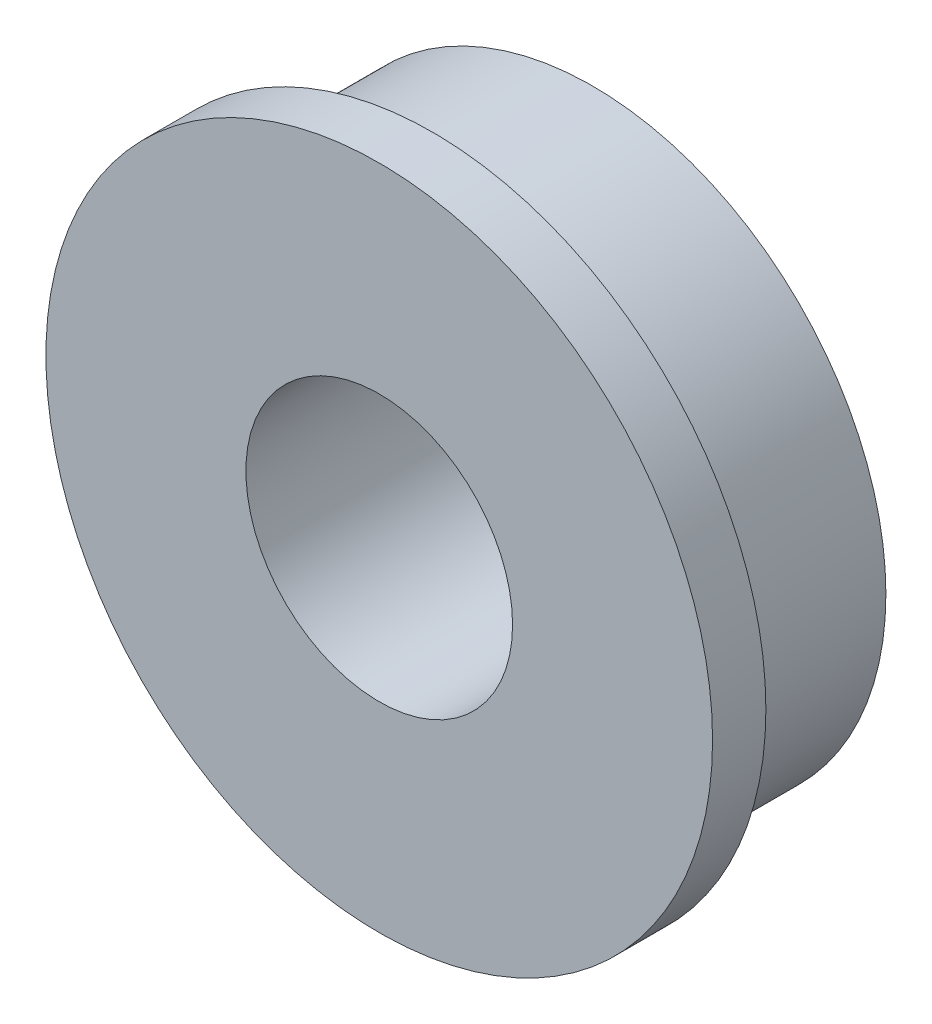
SolidWorks part; units mm, degrees
ref_plane "前视基准面" through (0, 0, 0) normal (0, 0, 1) x (1, 0, 0)
ref_plane "上视基准面" through (0, 0, 0) normal (0, 1, 0) x (1, 0, 0)
ref_plane "右视基准面" through (0, 0, 0) normal (1, 0, 0) x (0, 0, -1)
sketch "草图1" plane through (0, 0, 0) normal (0, 0, 1) x (1, 0, 0)
  circle A0 centre (0, 0) radius 5.5
  circle A1 centre (0, 0) radius 2.5
  dimension "D1" = 5
  dimension "D2" = 11
extrude "凸台-拉伸1" add sketch "草图1" along normal blind 3
sketch "草图2" plane through (0, 0, 3) normal (0, 0, 1) x (1, 0, 0)
  circle A0 centre (0, 0) radius 2.5
  circle A1 centre (0, 0) radius 6.25
  dimension "D1" = 12.5
extrude "凸台-拉伸2" add sketch "草图2" along normal blind 1
